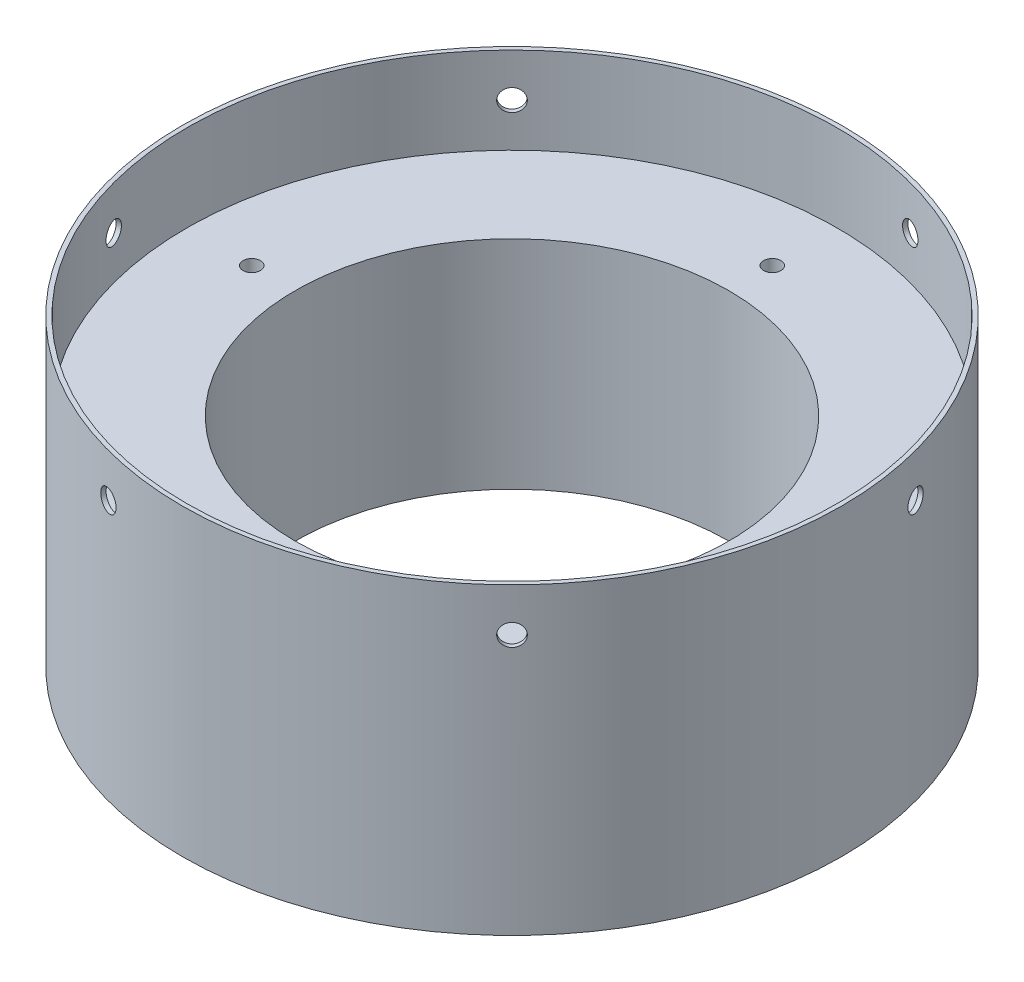
SolidWorks part; units mm, degrees
ref_plane "前基準面" through (0, 0, 0) normal (0, 0, 1) x (1, 0, 0)
ref_plane "上基準面" through (0, 0, 0) normal (0, 1, 0) x (1, 0, 0)
ref_plane "右基準面" through (0, 0, 0) normal (1, 0, 0) x (0, 0, -1)
sketch "草圖1" plane through (0, 0, 0) normal (0, 1, 0) x (1, 0, 0)
  circle A0 centre (0, 0) radius 76
  dimension "D1" = 152
extrude "填料-伸長1" add sketch "草圖1" along normal blind 70
sketch "草圖2" plane through (0, 70, 0) normal (0, 1, 0) x (1, 0, 0)
  circle A0 centre (0, 0) radius 75
  dimension "D1" = 150
extrude "除料-伸長1" cut sketch "草圖2" against normal blind 20
sketch "草圖3" plane through (0, 50, 0) normal (0, 1, 0) x (1, 0, 0)
  circle A0 centre (0, 0) radius 50
  dimension "D1" = 100
extrude "除料-伸長3" cut sketch "草圖3" against normal blind 50
sketch "草圖4" plane through (0, 0, 0) normal (0, -1, 0) x (1, 0, 0)
  line L0 (0, 0) -> (-60, 0)
  circle A0 centre (-60, 0) radius 2
  circle A1 centre (-42.4264, 42.4264) radius 2
  circle A2 centre (0, 60) radius 2
  circle A3 centre (42.4264, 42.4264) radius 2
  circle A4 centre (60, 0) radius 2
  circle A5 centre (42.4264, -42.4264) radius 2
  circle A6 centre (0, -60) radius 2
  circle A7 centre (-42.4264, -42.4264) radius 2
  point P23 (0, 0)
  dimension "D2" = 4
  dimension "D1" = 60
  dimension "D3" = 8
extrude "除料-伸長6" cut sketch "草圖4" against normal blind 70
sketch "草圖5" plane through (0, 0, 0) normal (0, -1, 0) x (-1, 0, 0)
  line L0 (0, 0) -> (-42.4264, 42.4264)
  circle A0 centre (-42.4264, 42.4264) radius 1
  dimension "D2" = 2
  dimension "D1" = 60
extrude "除料-伸長7" cut sketch "草圖5" against normal blind 10
pattern_circular "環狀複製排列1" count 4 over 360 about axis through (0, 0, 0) along (0, 1, 0) of "除料-伸長7"
hole_wizard "M6  螺絲攻的螺孔鑽1" positions "3D草圖1" profile "草圖7" hole size "M6" standard "IS"
sketch3d "3D草圖1"
  point P0 (53.7401, 60, 53.7401)
  point P3 (0, 0, 0)
sketch "草圖7" plane through (53.7401, 60, 53.7401) normal (0, 1, 0) x (0.7071, 0, -0.7071)
  line L0 (0, 0) -> (0, 36.5022)
  line L1 (0, 36.5022) -> (2.5, 35)
  line L2 (2.5, 35) -> (2.5, 0)
  line L5 (2.5, 0) -> (0, 0)
  line L10 (0, 36.5022) -> (-2.5, 35) construction
  line L11 (0, -6.35) -> (0, 107.95) construction
  dimension "鑽孔直徑" = 5
  dimension "鑽孔深度" = 35
  dimension "導頭角度" = 118
pattern_circular "環狀複製排列2" count 6 over 360 about axis through (0, 70, 0) along (0, 1, 0) of "M6  螺絲攻的螺孔鑽1"
